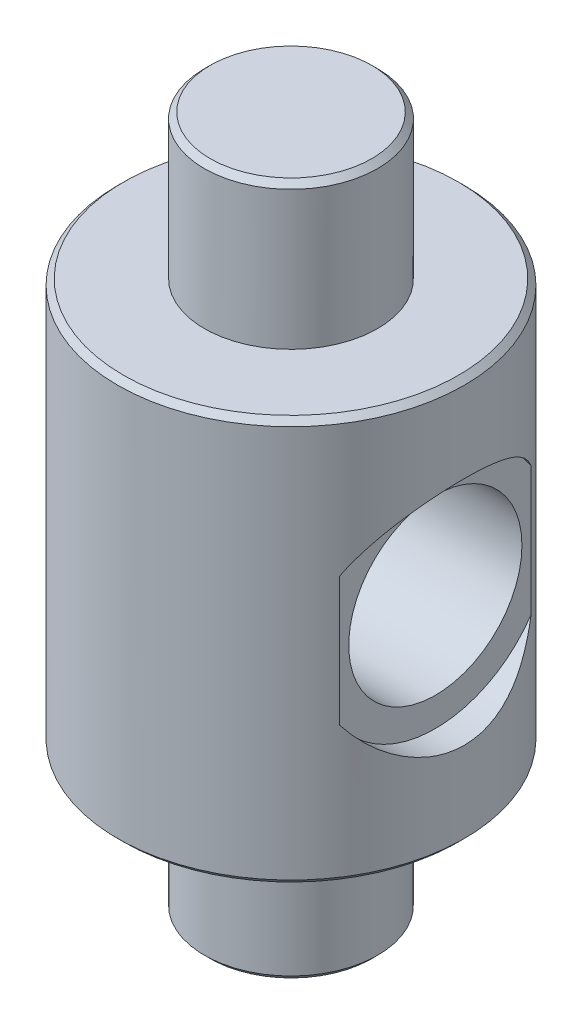
SolidWorks part; units mm, degrees
ref_plane "Front Plane" through (0, 0, 0) normal (0, 0, 1) x (1, 0, 0)
ref_plane "Top Plane" through (0, 0, 0) normal (0, 1, 0) x (1, 0, 0)
ref_plane "Right Plane" through (0, 0, 0) normal (1, 0, 0) x (0, 0, -1)
sketch "Sketch1" plane through (0, 0, 0) normal (0, 0, 1) x (1, 0, 0)
  line L0 (0, 0) -> (0, 12)
  line L1 (0, 12) -> (1.5, 12)
  line L2 (1.5, 12) -> (1.5, 9.5)
  line L3 (1.5, 9.5) -> (3, 9.5)
  line L4 (3, 9.5) -> (3, 2.5)
  line L5 (3, 2.5) -> (1.5, 2.5)
  line L6 (1.5, 2.5) -> (1.5, 0)
  line L7 (1.5, 0) -> (0, 0)
  dimension "D1" = 12
  dimension "D2" = 1.5
  dimension "D3" = 2.5
  dimension "D4" = 7
  dimension "D5" = 1.5
  dimension "D6" = 3
revolve "Revolve1" add sketch "Sketch1" angle 360 about L0
ref_plane "Plane1" through (3, 0, 0) normal (1, 0, 0) x (0, 0, -1)
sketch "Sketch6" plane through (3, 0, 0) normal (1, 0, 0) x (0, 0, -1)
  line L0 (-1.5, 0) -> (1.5, 0) construction
  circle A0 centre (0, 6) radius 2
  point P4 (0, 0)
  point P6 (0, 0)
  dimension "D1" = 6
extrude "Cut-Extrude1" cut sketch "Sketch6" against normal blind 0.5 contours A0
mirror "Mirror1" about plane through (0, 0, 0) normal (1, 0, 0) of "Cut-Extrude1"
sketch "Sketch7" plane through (2.5, 0, 0) normal (1, 0, 0) x (0, 0, -1)
  circle A0 centre (0, 6) radius 1.5
extrude "Cut-Extrude2" cut sketch "Sketch7" against normal through all
chamfer "Chamfer1" distance 0.1 angle 45 4 edges at (0, 0, -1.5) (0, 2.5, -3) (0, 9.5, -3) (0, 12, -1.5)
